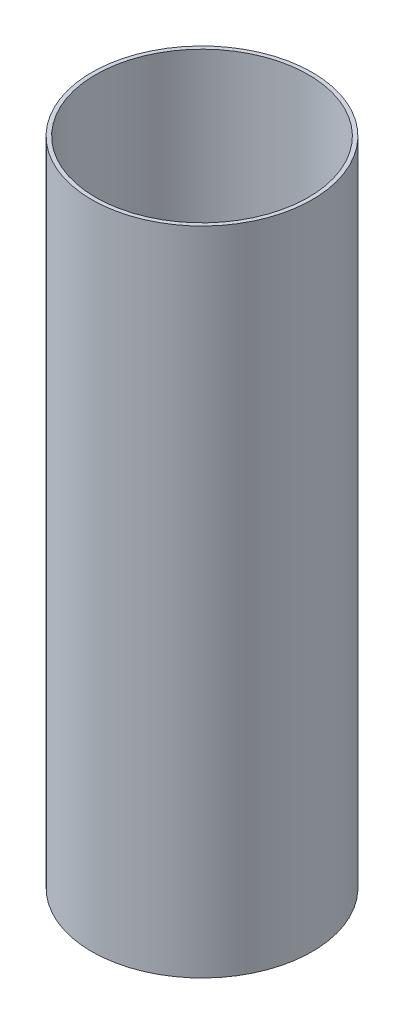
SolidWorks part; units mm, degrees
ref_plane "Front Plane" through (0, 0, 0) normal (0, 0, 1) x (1, 0, 0)
ref_plane "Top Plane" through (0, 0, 0) normal (0, 1, 0) x (1, 0, 0)
ref_plane "Right Plane" through (0, 0, 0) normal (1, 0, 0) x (0, 0, -1)
sketch "Sketch1" plane through (0, 0, 0) normal (0, 1, 0) x (1, 0, 0)
  circle A0 centre (0, 0) radius 49
  circle A1 centre (0, 0) radius 50.8
  dimension "D1" = 98
  dimension "D2" = 101.6
extrude "Boss-Extrude1" add sketch "Sketch1" along normal blind 300
